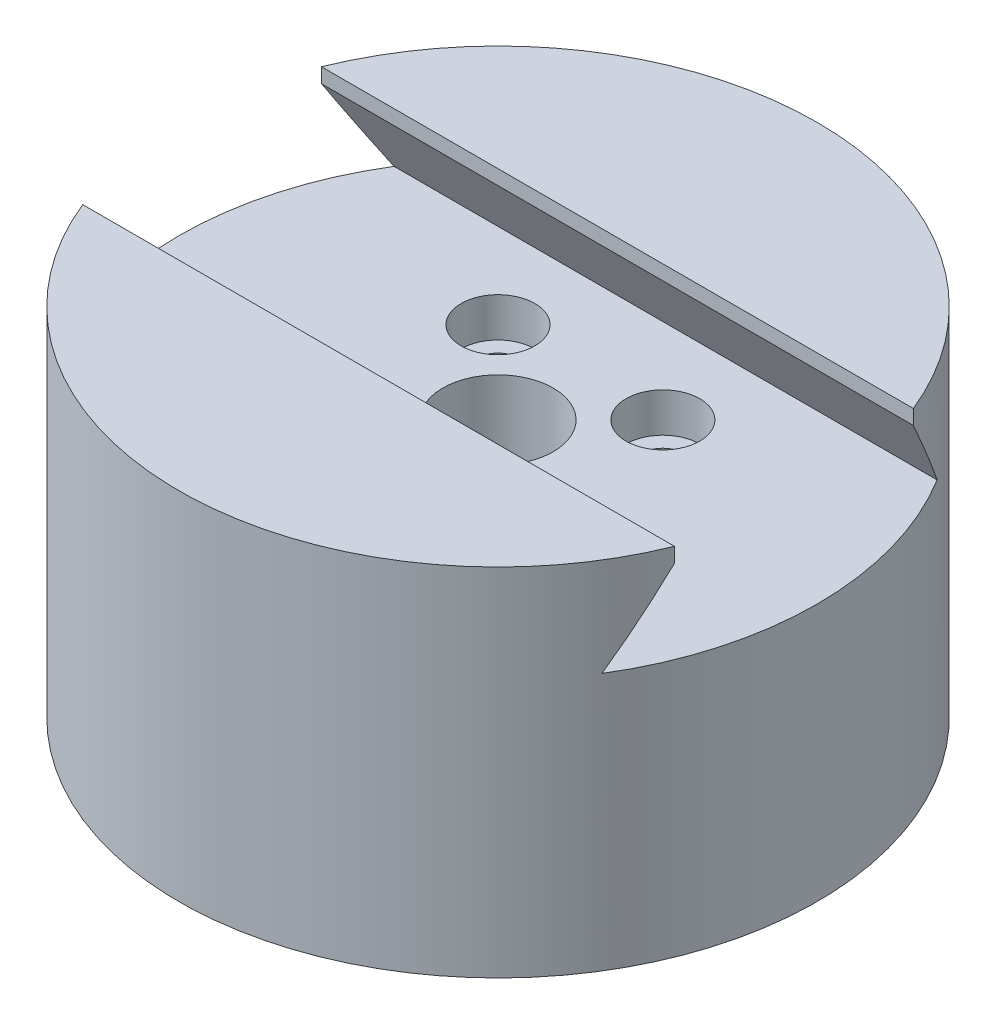
SolidWorks part; units mm, degrees
material "3.1355 (EN-AW 2024)"
ref_plane "Спереди" through (0, 0, 0) normal (0, 0, 1) x (1, 0, 0)
ref_plane "Сверху" through (0, 0, 0) normal (0, 1, 0) x (1, 0, 0)
ref_plane "Справа" through (0, 0, 0) normal (1, 0, 0) x (0, 0, -1)
sketch "Эскиз1" plane through (0, 0, 0) normal (0, 1, 0) x (1, 0, 0)
  circle A0 centre (0, 0) radius 26
  dimension "D1" = 52
extrude "Бобышка-Вытянуть1" add sketch "Эскиз1" along normal blind 14
sketch "Эскиз2" plane through (0, 0, 0) normal (1, 0, 0) x (0, 0, -1)
  line L0 (0, 14) -> (0, 0) construction
  line L1 (26, 14) -> (-26, 14) construction
  line L2 (13.6547, 6) -> (-13.6547, 6)
  line L3 (-13.6547, 6) -> (-9.7287, 12.8)
  line L4 (-9.7287, 12.8) -> (-9.7287, 14)
  line L5 (-9.7287, 14) -> (9.7287, 14)
  line L6 (0, 14) -> (0, 6) construction
  line L7 (13.6547, 6) -> (9.7287, 12.8)
  line L8 (9.7287, 12.8) -> (9.7287, 14)
  line L9 (-12.5, 8) -> (-12.5, 6) construction
  dimension "D1" = 8
  dimension "D2" = 1.2
  dimension "D3" = 60
  dimension "D4" = 13.6547
  dimension "D5" = 9.7287
  dimension "D6" = 2
  dimension "D7" = 12.5
extrude "Вырез-Вытянуть1" cut sketch "Эскиз2" against normal mid plane 60
sketch "Примерка" plane through (0, 0, 0) normal (1, 0, 0) x (0, 0, -1)
  line L0 (13.6547, 6) -> (-13.6547, 6) construction
  line L1 (-12.5, 14) -> (12.5, 14)
  line L2 (-12.5, 14) -> (-12.5, 6)
  line L3 (-12.5, 6) -> (12.5, 6)
  line L4 (12.5, 14) -> (12.5, 6)
  point P6 (0, 6)
  dimension "D1" = 8
  dimension "D2" = 25
sketch "Эскиз4" plane through (0, 0, 0) normal (0, -1, 0) x (1, 0, 0)
  circle A0 centre (0, 0) radius 4.5
  dimension "D1" = 9
extrude "Вырез-Вытянуть2" cut sketch "Эскиз4" against normal through all
sketch "Эскиз5" plane through (0, 0, 0) normal (0, -1, 0) x (1, 0, 0)
  line L2 (-22.1258, -15.6547) -> (22.1258, -15.6547)
  line L3 (-18.0594, -15.6547) -> (18.0594, -15.6547)
  circle A2 centre (0, 0) radius 23.9
  arc A3 (-18.0594, -15.6547) -> (18.0594, -15.6547) centre (0, 0) ccw
  dimension "D1" = 2.1
  dimension "D2" = 2
extrude "Вырез-Вытянуть3" cut sketch "Эскиз5" against normal offset from surface (12 mm away) 2 up to face at (0, 14, -17.8644)
sketch "Эскиз6" plane through (0, 6, 0) normal (0, 1, 0) x (1, 0, 0)
  line L0 (0, -12.5) -> (0, 12.5) construction
  line L1 (0, 0) -> (6.7175, 6.7175) construction
  line L2 (0, 0) -> (9.5, 0) construction
  line L3 (0, 0) -> (6.7175, -6.7175) construction
  line L4 (0, 0) -> (-6.7175, -6.7175) construction
  line L5 (0, 0) -> (-6.7175, 6.7175) construction
  circle A0 centre (0, 0) radius 9.5
  point P12 (0, 0)
  dimension "D1" = 19
  dimension "D2" = 45
  dimension "D3" = 4
hole_wizard "Цековка для винта с внутренним шестигранником M31" positions "Эскиз8" profile "Эскиз7" counterbore size "M3" standard "Ansi Metric" end condition through all
sketch "Эскиз8" plane through (0, 6, 0) normal (0, 1, 0) x (1, 0, 0)
  point P0 (-6.7175, 6.7175)
  point P3 (6.7175, 6.7175)
  point P6 (6.7175, -6.7175)
  point P9 (-6.7175, -6.7175)
sketch "Эскиз7" plane through (-6.7175, 6, -6.7175) normal (1, 0, 0) x (0, 0, 1)
  line L0 (0, 0) -> (0, 6)
  line L1 (0, 6) -> (1.7, 6)
  line L3 (1.7, 6) -> (1.7, 3.2)
  line L4 (1.7, 3.2) -> (3, 3.2)
  line L5 (3, 3.2) -> (3, 0)
  line L7 (3, 0) -> (0, 0)
  line L11 (0, -6.35) -> (0, 107.95) construction
  dimension "Диаметр сквозного отверстия" = 3.4
  dimension "Глубина сквозного отверстия" = 6
  dimension "Диаметр цековки" = 6
  dimension "Глубина цековки" = 3.2
sketch "Эскиз12" plane through (0, 0, 0) normal (0, -1, 0) x (1, 0, 0)
  circle A0 centre (0, 0) radius 26 construction
  circle A1 centre (0, 0) radius 26
  circle A3 centre (0, 0) radius 24
  dimension "D1" = 2
extrude "Бобышка-Вытянуть2" add sketch "Эскиз12" along normal blind 15
